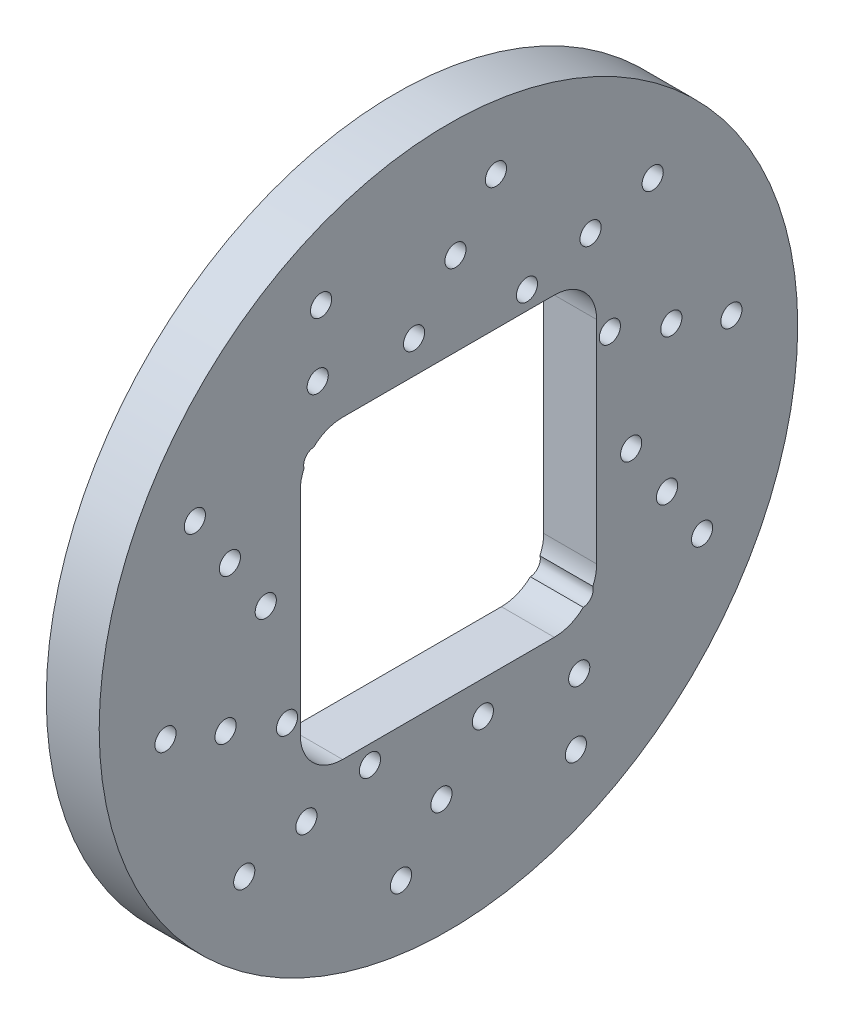
SolidWorks part; units mm, degrees
material "Cast Alloy Steel"
ref_plane "Front Plane" through (0, 0, 0) normal (0, 0, 1) x (1, 0, 0)
ref_plane "Top Plane" through (0, 0, 0) normal (0, 1, 0) x (1, 0, 0)
ref_plane "Right Plane" through (0, 0, 0) normal (1, 0, 0) x (0, 0, -1)
sketch "Sketch1" plane through (0, 0, 0) normal (1, 0, 0) x (0, 0, -1)
  circle A0 centre (0, 0) radius 16.5
  dimension "D1" = 33
extrude "Boss-Extrude1" add sketch "Sketch1" along normal blind 2.5
sketch "Sketch2" plane through (2.5, 0, 0) normal (1, 0, 0) x (0, 0, -1)
  line L1 (-7, 7) -> (7, 7)
  line L2 (-7, 7) -> (-7, -7)
  line L3 (-7, -7) -> (7, -7)
  line L4 (7, 7) -> (7, -7)
  line L5 (-7, 7) -> (7, -7) construction
  line L6 (-7, -7) -> (7, 7) construction
  point P0 (0, 0)
  dimension "D1" = 14
  dimension "D2" = 14
extrude "Cut-Extrude2" cut sketch "Sketch2" against normal blind 2.5
fillet "Fillet1" radius 2 4 edges at (1.25, -7, 7) (1.25, -7, -7) (1.25, 7, -7) (1.25, 7, 7)
sketch "Sketch5" plane through (2.5, 0, 0) normal (1, 0, 0) x (0, 0, -1)
  line L0 (-1.6259, 8.5469) -> (3.8432, 15.3029) construction
  circle A0 centre (-1.6259, 8.5469) radius 0.5
  circle A1 centre (0.3309, 10.9642) radius 0.5
  circle A2 centre (2.2429, 13.326) radius 0.5
  point P0 (0, 0)
  dimension "D1" = 1
  dimension "D2" = 1
  dimension "D3" = 1
extrude "Cut-Extrude3" cut sketch "Sketch5" against normal blind 2.5
sketch "Sketch6" plane through (0, 0, 0) normal (0, 1, 0) x (1, 0, 0)
  line L0 (2.5, 0) -> (15.5667, 0) construction
  line L1 (2.5, -16.5) -> (2.5, 16.5) construction
pattern_circular "CirPattern3" count 10 over 360 about axis through (0, 0, 0) along (1, 0, 0) of "Cut-Extrude3"
